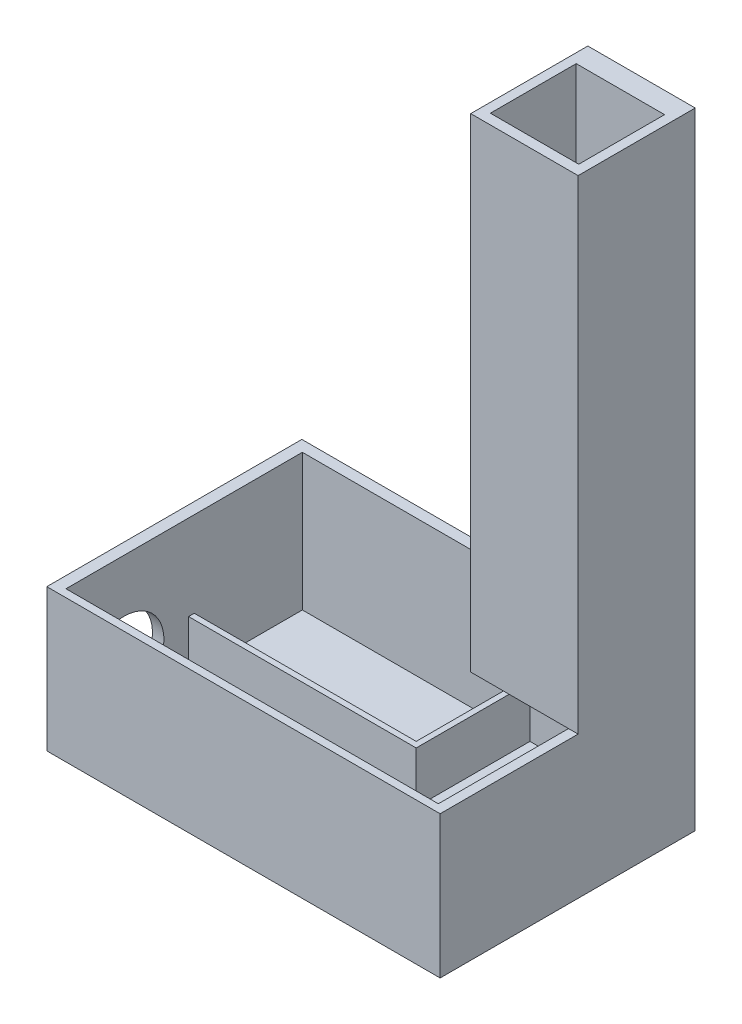
SolidWorks part; units mm, degrees
ref_plane "Front Plane" through (0, 0, 0) normal (0, 0, 1) x (1, 0, 0)
ref_plane "Top Plane" through (0, 0, 0) normal (0, 1, 0) x (1, 0, 0)
ref_plane "Right Plane" through (0, 0, 0) normal (1, 0, 0) x (0, 0, -1)
sketch "Sketch1" plane through (0, 0, 0) normal (0, 1, 0) x (1, 0, 0)
  line L1 (0, 0) -> (13.8249, 0)
  line L2 (0, 0) -> (0, -8.9649)
  line L3 (0, -8.9649) -> (13.8249, -8.9649)
  line L4 (13.8249, 0) -> (13.8249, -8.9649)
extrude "Boss-Extrude1" add sketch "Sketch1" along normal blind 5
sketch "Sketch2" plane through (0, 5, 0) normal (0, 1, 0) x (1, 0, 0)
  line L1 (0.4013, -0.3833) -> (13.4899, -0.3833)
  line L2 (0.4013, -0.3833) -> (0.4013, -8.6927)
  line L3 (0.4013, -8.6927) -> (13.4899, -8.6927)
  line L4 (13.4899, -0.3833) -> (13.4899, -8.6927)
extrude "Cut-Extrude1" cut sketch "Sketch2" against normal blind 4.8
sketch "Sketch3" plane through (0, 0.2, 0) normal (0, 1, 0) x (1, 0, 0)
  line L0 (13.4899, -0.3833) -> (0.4013, -0.3833) construction
  line L1 (0.4013, -0.3833) -> (8.2013, -0.3833)
  line L2 (0.4013, -0.3833) -> (0.4013, -4.1833)
  line L3 (0.4013, -4.1833) -> (8.2013, -4.1833)
  line L4 (8.2013, -0.3833) -> (8.2013, -4.1833)
  line L6 (0.4013, -0.3833) -> (8.4013, -0.3833)
  line L7 (0.4013, -0.3833) -> (0.4013, -4.3833)
  line L8 (0.4013, -4.3833) -> (8.4013, -4.3833)
  line L9 (8.4013, -0.3833) -> (8.4013, -4.3833)
  line M9 (0.4013, -0.3833) -> (0.4013, -8.6927)
  line M12 (13.4899, -0.3833) -> (0.4013, -0.3833)
  dimension "D1" = 7.8
  dimension "D2" = 8
  dimension "D3" = 3.8
  dimension "D4" = 4
extrude "Boss-Extrude2" add sketch "Sketch3" along normal blind 1.8 contours L9 L4 L3 L8 M12 M9
sketch "Sketch4" plane through (0, 0, 0) normal (-1, 0, 0) x (0, 0, 1)
  circle A0 centre (6.6519, 1.7423) radius 1.4
extrude "Cut-Extrude3" cut sketch "Sketch4" against normal blind 1.8
sketch "Sketch7" plane through (0, 0.2, 0) normal (0, 1, 0) x (1, 0, 0)
  line L1 (13.0588, -8.3123) -> (12.618, -8.3123)
  line L2 (13.0588, -8.3123) -> (13.0588, -6.0416)
  line L3 (13.0588, -6.0416) -> (12.618, -6.0416)
  line L4 (12.618, -8.3123) -> (12.618, -6.0416)
extrude "Cut-Extrude4" cut sketch "Sketch7" against normal through all
sketch "Sketch9" plane through (0, 5, 0) normal (0, 1, 0) x (1, 0, 0)
  line L1 (13.4899, -8.6927) -> (13.4899, -0.3833) construction
  line L2 (13.4899, -3.758) -> (10.3832, -3.758)
  line L5 (13.4899, -4.1156) -> (10.0509, -4.1156)
  line L6 (10.0509, -4.1156) -> (10.0509, -0.3833)
  line L7 (13.4899, -0.3833) -> (0.4013, -0.3833) construction
  line L10 (13.4899, -4.1156) -> (13.8249, -4.1156)
  line L11 (13.8249, -8.9649) -> (13.8249, 0) construction
  line L12 (13.8249, -4.1156) -> (13.8249, 0)
  line L13 (13.8249, 0) -> (10.0509, 0)
  line L14 (13.8249, 0) -> (0, 0) construction
  line L15 (10.0509, 0) -> (10.0509, -0.3833)
  line L18 (10.3832, -0.7406) -> (13.4899, -0.7406)
  line L19 (10.3832, -0.7406) -> (10.3832, -3.758)
  line L20 (13.4899, -0.7406) -> (13.4899, -3.758)
extrude "Boss-Extrude3" add sketch "Sketch9" along normal blind 17
sketch "Sketch11" plane through (0, 0, 0) normal (0, 0, -1) x (-1, 0, 0)
  line L7 (-10.0509, 4.9396) -> (-10.0509, 4.4)
  line L10 (-13.3666, 4.9396) -> (-13.3666, 4.4)
  line L13 (-13.3666, 4.4) -> (-10.0509, 4.4)
  line L14 (-10.0509, 4.9396) -> (-13.3666, 4.9396)
extrude "Cut-Extrude11" cut sketch "Sketch11" against normal blind 1
